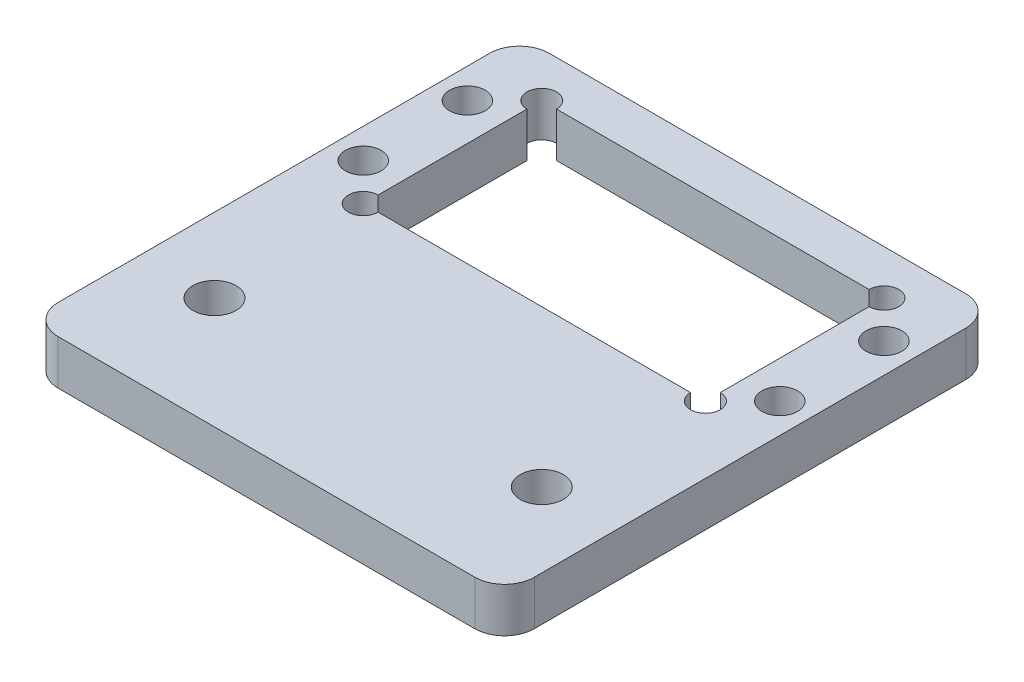
SolidWorks part; units mm, degrees
material "Thornel Mat VMA"
ref_plane "前视基准面" through (0, 0, 0) normal (0, 0, 1) x (1, 0, 0)
ref_plane "上视基准面" through (0, 0, 0) normal (0, 1, 0) x (1, 0, 0)
ref_plane "右视基准面" through (0, 0, 0) normal (1, 0, 0) x (0, 0, -1)
other "Configuration Table"
sketch "草图1" plane through (0, 0, 0) normal (0, 1, 0) x (1, 0, 0)
  line L1 (-16, -9) -> (16, -9)
  line L2 (-16, -9) -> (-16, 9)
  line L3 (-16, 9) -> (16, 9)
  line L4 (16, -9) -> (16, 9)
  line L5 (-16, -9) -> (16, 9) construction
  line L6 (-16, 9) -> (16, -9) construction
  line L7 (-14, -3.5) -> (14, -3.5) construction
  line L8 (-14, -3.5) -> (-14, 3.5) construction
  line L9 (-14, 3.5) -> (14, 3.5) construction
  line L10 (14, -3.5) -> (14, 3.5) construction
  line L11 (-14, -3.5) -> (14, 3.5) construction
  line L12 (-14, 3.5) -> (14, -3.5) construction
  line L13 (-11.5, -6) -> (11.5, -6)
  line L14 (-11.5, -6) -> (-11.5, 6)
  line L15 (-11.5, 6) -> (11.5, 6)
  line L16 (11.5, -6) -> (11.5, 6)
  line L17 (-11.5, -6) -> (11.5, 6) construction
  line L18 (-11.5, 6) -> (11.5, -6) construction
  circle A0 centre (-14, 3.5) radius 1.2
  circle A1 centre (-14, -3.5) radius 1.2
  circle A2 centre (14, 3.5) radius 1.2
  circle A3 centre (14, -3.5) radius 1.2
  point P0 (0, 0)
  point P5 (0, 0)
  point P15 (0, 0)
  dimension "D5" = 2.4
  dimension "D6" = 2.4
  dimension "D7" = 2.4
  dimension "D8" = 2.4
  dimension "D1" = 18
  dimension "D2" = 32
  dimension "D3" = 7
  dimension "D4" = 28
  dimension "D9" = 12
  dimension "D10" = 23
extrude "凸台-拉伸1" add sketch "草图1" along normal blind 3
sketch "草图2" plane through (0, 3, 0) normal (0, 1, 0) x (1, 0, 0)
  circle A0 centre (-11.5, 6) radius 1
  circle A1 centre (-11.5, -6) radius 1
  circle A2 centre (11.5, -6) radius 1
  circle A3 centre (11.5, 6) radius 1
  dimension "D1" = 2
  dimension "D2" = 2
  dimension "D3" = 2
  dimension "D4" = 2
extrude "切除-拉伸1" cut sketch "草图2" against normal up to next
sketch "草图4" plane through (0, 3, 0) normal (0, 1, 0) x (1, 0, 0)
  line L0 (16, -9) -> (16, 9) construction
  line L1 (-16, -9) -> (16, -9)
  line L2 (-16, -9) -> (-16, -24)
  line L3 (-16, -24) -> (16, -24)
  line L4 (16, -9) -> (16, -24)
  line L5 (-16, -16.5) -> (16, -16.5) construction
  circle A0 centre (-11, -16.5) radius 1.45
  circle A1 centre (11, -16.5) radius 1.45
  dimension "D2" = 2.9
  dimension "D3" = 2.9
  dimension "D5" = 5
  dimension "D1" = 15
  dimension "D4" = 5
extrude "凸台-拉伸2" add sketch "草图4" against normal blind 3
fillet "圆角1" radius 2 4 edges at (16, 1.5, -9) (-16, 1.5, -9) (-16, 1.5, 24) (16, 1.5, 24)
